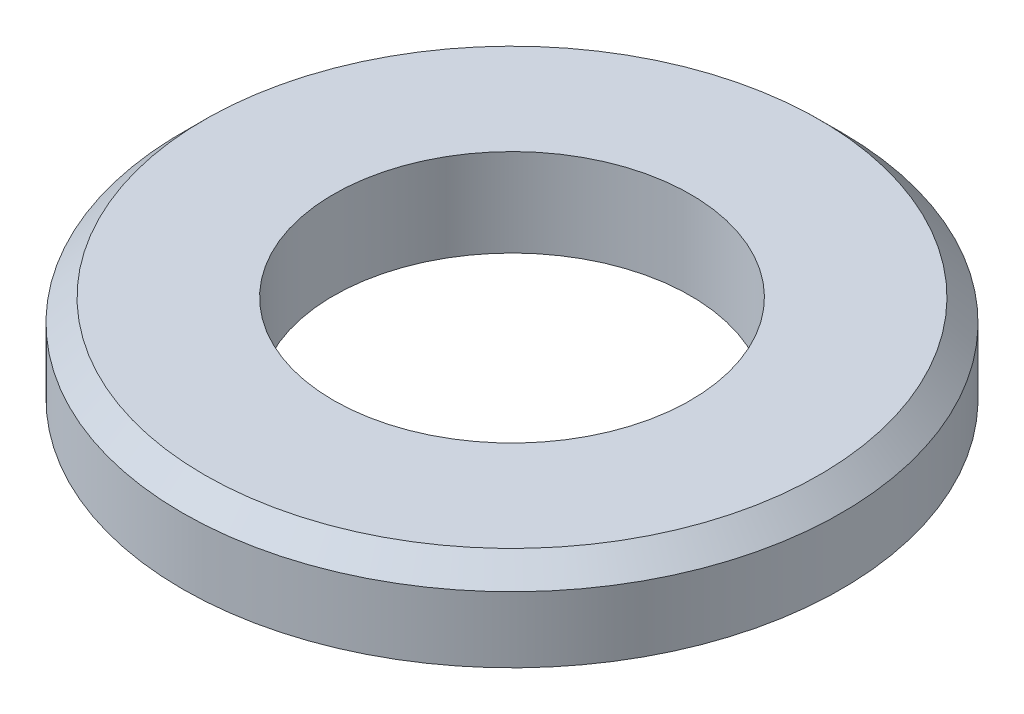
SolidWorks part; units mm, degrees
ref_plane "前视基准面" through (0, 0, 0) normal (0, 0, 1) x (1, 0, 0)
ref_plane "上视基准面" through (0, 0, 0) normal (0, 1, 0) x (1, 0, 0)
ref_plane "右视基准面" through (0, 0, 0) normal (1, 0, 0) x (0, 0, -1)
sketch "草图1" plane through (0, 0, 0) normal (0, 1, 0) x (1, 0, 0)
  circle A0 centre (0, 0) radius 6
  circle A1 centre (0, 0) radius 3.25
  dimension "D1" = 12
  dimension "D2" = 6.5
extrude "凸台-拉伸1" add sketch "草图1" along normal blind 1.6
chamfer "倒角1" distance 0.4 angle 45 1 edges at (0, 1.6, 6)
